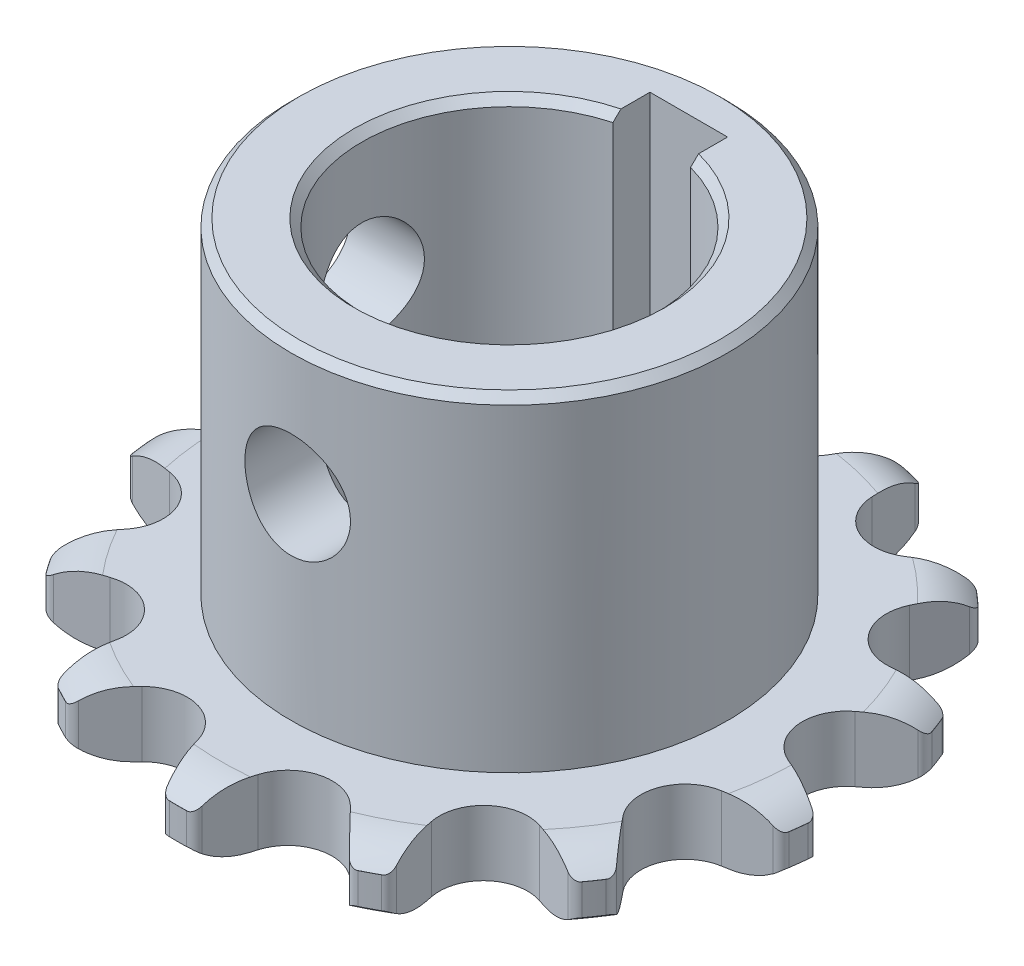
SolidWorks part; units mm, degrees
ref_plane "Alzado" through (0, 0, 0) normal (0, 0, 1) x (1, 0, 0)
ref_plane "Planta" through (0, 0, 0) normal (0, 1, 0) x (1, 0, 0)
ref_plane "Vista lateral" through (0, 0, 0) normal (1, 0, 0) x (0, 0, -1)
sketch "Croquis1" plane through (0, 0, 0) normal (0, 1, 0) x (1, 0, 0)
  circle A0 centre (0, 0) radius 14.05
  circle A1 centre (0, 0) radius 9.5
  dimension "D1" = 19
  dimension "D2" = 28.1
extrude "Saliente-Extruir1" add sketch "Croquis1" along normal blind 25.2
sketch "Croquis2" plane through (0, 25.2, 0) normal (0, 1, 0) x (1, 0, 0)
  line L0 (0, 11.55) -> (0, 14.05) construction
  line L1 (-2.5, 11.55) -> (2.5, 11.55)
  line L2 (-2.5, 11.55) -> (-2.5, 7.7298)
  line L3 (-2.5, 7.7298) -> (2.5, 7.7298)
  line L4 (2.5, 11.55) -> (2.5, 7.7298)
  circle A0 centre (0, 0) radius 14.05 construction
  point P4 (0, 11.55)
  dimension "D1" = 2.5
  dimension "D2" = 5
extrude "Cortar-Extruir1" cut sketch "Croquis2" against normal through all
sketch "Croquis4" plane through (0, 0, 0) normal (0, 0, 1) x (1, 0, 0)
  line L0 (0, 16.8) -> (0, 20.2) construction
  line L1 (9.5, 25.2) -> (-9.5, 25.2) construction
  circle A0 centre (0, 16.8) radius 3.4
  dimension "D2" = 6.8
  dimension "D1" = 5
extrude "Cortar-Extruir2" cut sketch "Croquis4" along normal through all
sketch "Croquis5" plane through (0, 0, 0) normal (1, 0, 0) x (0, 0, -1)
  line L0 (0, 16.8) -> (0, 20.2) construction
  line L1 (14.05, 25.2) -> (-14.05, 25.2) construction
  circle A0 centre (0, 16.8) radius 3.4
  dimension "D2" = 6.8
  dimension "D1" = 5
extrude "Cortar-Extruir3" cut sketch "Croquis5" against normal through all
sketch "Croquis6" plane through (0, 0, 0) normal (0, -1, 0) x (1, 0, 0)
  circle A0 centre (0, 0) radius 21.35
  circle A3 centre (0, 0) radius 12.05
  circle A4 centre (0, 0) radius 12.05
  dimension "D1" = 42.7
  dimension "D2" = 2
extrude "Saliente-Extruir2" add sketch "Croquis6" against normal blind 4.2
chamfer "Chaflán1" distance 0.5 angle 45 3 edges at (0, 25.2, 14.05) (0, 25.2, 9.5) (0, 0, 9.5)
sketch "Croquis8" plane through (0, 4.2, 0) normal (0, 1, 0) x (1, 0, 0)
  line L0 (0, 19.5) -> (0, 16.65) construction
  line L1 (2.5, 11.55) -> (-2.5, 11.55) construction
  circle A0 centre (0, 19.5) radius 2.85
  circle A1 centre (9.0621, 17.2664) radius 2.85
  circle A2 centre (16.0482, 11.0773) radius 2.85
  circle A3 centre (19.3578, 2.3505) radius 2.85
  circle A4 centre (18.2328, -6.9148) radius 2.85
  circle A5 centre (12.9309, -14.596) radius 2.85
  circle A6 centre (4.6667, -18.9334) radius 2.85
  circle A7 centre (-4.6667, -18.9334) radius 2.85
  circle A8 centre (-12.9309, -14.596) radius 2.85
  circle A9 centre (-18.2328, -6.9148) radius 2.85
  circle A10 centre (-19.3578, 2.3505) radius 2.85
  circle A11 centre (-16.0482, 11.0773) radius 2.85
  circle A12 centre (-9.0621, 17.2664) radius 2.85
  circle A13 centre (0, 0) radius 14.05 construction
  dimension "D2" = 5.7
  dimension "D4" = 4.6667
  dimension "D1" = 5.1
  dimension "D5" = 12.9309
  dimension "D6" = 16.0482
  dimension "D7" = 18.2328
  dimension "D8" = 19.3578
  dimension "D9" = 4.6667
  dimension "D10" = 9.0621
  dimension "D11" = 12.9309
  dimension "D12" = 16.0482
  dimension "D13" = 18.2328
  dimension "D14" = 19.3578
  dimension "D15" = 2.3505
  dimension "D3" = 9.0621
  dimension "D16" = 11.0773
  dimension "D17" = 17.2664
  dimension "D18" = 6.9148
  dimension "D19" = 14.596
  dimension "D20" = 18.9334
extrude "Cortar-Extruir4" cut sketch "Croquis8" against normal through all
sketch "Croquis9" plane through (0, 4.2, 0) normal (0, 1, 0) x (1, 0, 0)
  line L0 (2.4655, 18.0703) -> (4.1331, 20.9461)
  line L1 (6.0745, 20.4676) -> (6.2146, 17.1462)
  line L4 (2.2653, 21.2295) -> (3.6331, 21.8461)
  line L5 (3.6331, 21.8461) -> (4.1331, 20.9461)
  line L6 (6.0745, 20.4676) -> (6.5745, 21.216)
  line L7 (6.5745, 21.216) -> (7.8601, 19.8505)
  line L8 (13.3694, 17.6554) -> (13.3938, 16.6261)
  line L9 (10.5807, 14.8547) -> (13.3938, 16.6261)
  line L10 (11.8716, 17.7451) -> (13.3694, 17.6554)
  line L11 (15.6809, 15.7305) -> (16.1847, 13.924)
  line L12 (14.8904, 15.3002) -> (13.471, 12.2941)
  line L13 (14.8904, 15.3002) -> (15.6809, 15.7305)
  line L14 (20.0428, 9.42) -> (19.5862, 8.4973)
  line L15 (16.2721, 8.2361) -> (19.5862, 8.4973)
  line L16 (18.7583, 10.1955) -> (20.0428, 9.42)
  line L17 (21.1951, 6.6414) -> (20.8017, 4.8077)
  line L18 (20.2952, 6.6277) -> (17.6414, 4.6256)
  line L19 (20.2952, 6.6277) -> (21.1951, 6.6414)
  line L20 (22.1248, -0.9734) -> (21.2916, -1.5782)
  line L21 (18.2357, -0.2693) -> (21.2916, -1.5782)
  line L22 (21.3477, 0.3102) -> (22.1248, -0.9734)
  line L23 (21.8537, -3.9692) -> (20.6532, -5.41)
  line L24 (21.0506, -3.5631) -> (17.7703, -4.1026)
  line L25 (21.0506, -3.5631) -> (21.8537, -3.9692)
  line L26 (19.1382, -11.1438) -> (18.1193, -11.2921)
  line L27 (16.0218, -8.7131) -> (18.1193, -11.2921)
  line L28 (19.0466, -9.6461) -> (19.1382, -11.1438)
  line L29 (17.5059, -13.6705) -> (15.7733, -14.3884)
  line L30 (16.9835, -12.9376) -> (13.8283, -11.8909)
  line L31 (16.9835, -12.9376) -> (17.5059, -13.6705)
  line L32 (11.7672, -18.7613) -> (10.7962, -18.4192)
  line L33 (10.1374, -15.1607) -> (10.7962, -18.4192)
  line L34 (12.3822, -17.3926) -> (11.7672, -18.7613)
  line L35 (9.1477, -20.24) -> (7.28, -20.0705)
  line L36 (9.0257, -19.3483) -> (6.7183, -16.9552)
  line L37 (9.0257, -19.3483) -> (9.1477, -20.24)
  line L38 (1.7006, -22.0808) -> (0.9997, -21.3266)
  line L39 (1.9307, -18.1352) -> (0.9997, -21.3266)
  line L40 (2.8811, -21.1547) -> (1.7006, -22.0808)
  line L41 (-1.3061, -22.1728) -> (-2.8811, -21.1547)
  line L42 (-0.9997, -21.3266) -> (-1.9307, -18.1352)
  line L43 (-0.9997, -21.3266) -> (-1.3061, -22.1728)
  line L44 (-8.7557, -20.3419) -> (-9.0257, -19.3483)
  line L45 (-6.7183, -16.9552) -> (-9.0257, -19.3483)
  line L46 (-7.28, -20.0705) -> (-8.7557, -20.3419)
  line L47 (-11.4607, -19.0261) -> (-12.3822, -17.3926)
  line L48 (-10.7962, -18.4192) -> (-10.1374, -15.1607)
  line L49 (-10.7962, -18.4192) -> (-11.4607, -19.0261)
  line L50 (-17.2061, -13.9429) -> (-16.9835, -12.9376)
  line L51 (-13.8283, -11.8909) -> (-16.9835, -12.9376)
  line L52 (-15.7733, -14.3884) -> (-17.2061, -13.9429)
  line L53 (-18.9898, -11.5207) -> (-19.0466, -9.6461)
  line L54 (-18.1193, -11.2921) -> (-16.0218, -8.7131)
  line L55 (-18.1193, -11.2921) -> (-18.9898, -11.5207)
  line L56 (-21.7148, -4.3497) -> (-21.0506, -3.5631)
  line L57 (-17.7703, -4.1026) -> (-21.0506, -3.5631)
  line L58 (-20.6532, -5.41) -> (-21.7148, -4.3497)
  line L59 (-22.1686, -1.3761) -> (-21.3477, 0.3102)
  line L60 (-21.2916, -1.5782) -> (-18.2357, -0.2693)
  line L61 (-21.2916, -1.5782) -> (-22.1686, -1.3761)
  line L62 (-21.2489, 6.2399) -> (-20.2952, 6.6277)
  line L63 (-17.6414, 4.6256) -> (-20.2952, 6.6277)
  line L64 (-20.8017, 4.8077) -> (-21.2489, 6.2399)
  line L65 (-20.2688, 9.0838) -> (-18.7583, 10.1955)
  line L66 (-19.5862, 8.4973) -> (-16.2721, 8.2361)
  line L67 (-19.5862, 8.4973) -> (-20.2688, 9.0838)
  line L68 (-15.9152, 15.4) -> (-14.8904, 15.3002)
  line L69 (-13.471, 12.2941) -> (-14.8904, 15.3002)
  line L70 (-16.1847, 13.924) -> (-15.9152, 15.4)
  line L71 (-13.7257, 17.4627) -> (-11.8716, 17.7451)
  line L72 (-13.3938, 16.6261) -> (-10.5807, 14.8547)
  line L73 (-13.3938, 16.6261) -> (-13.7257, 17.4627)
  line L74 (-6.9354, 21.0322) -> (-6.0745, 20.4676)
  line L75 (-6.2146, 17.1462) -> (-6.0745, 20.4676)
  line L76 (-7.8601, 19.8505) -> (-6.9354, 21.0322)
  line L77 (-4.0381, 21.8411) -> (-2.2653, 21.2295)
  line L78 (-4.1331, 20.9461) -> (-2.4655, 18.0703)
  line L79 (-4.1331, 20.9461) -> (-4.0381, 21.8411)
  arc A0 (-2.2653, 21.2295) -> (2.2653, 21.2295) centre (0, 19.5) ccw construction
  arc A1 (7.8601, 19.8505) -> (2.2653, 21.2295) centre (0, 0) ccw construction
  arc A2 (10.5807, 14.8547) -> (11.8716, 17.7451) centre (9.0621, 17.2664) ccw
  arc A3 (7.8601, 19.8505) -> (11.8716, 17.7451) centre (9.0621, 17.2664) ccw construction
  arc A4 (7.8601, 19.8505) -> (6.2146, 17.1462) centre (9.0621, 17.2664) ccw
  arc A5 (2.4655, 18.0703) -> (2.2653, 21.2295) centre (0, 19.5) ccw
  arc A6 (16.1847, 13.924) -> (13.471, 12.2941) centre (16.0482, 11.0773) ccw
  arc A7 (16.2721, 8.2361) -> (18.7583, 10.1955) centre (16.0482, 11.0773) ccw
  arc A8 (20.8017, 4.8077) -> (17.6414, 4.6256) centre (19.3578, 2.3505) ccw
  arc A9 (18.2357, -0.2693) -> (21.3477, 0.3102) centre (19.3578, 2.3505) ccw
  arc A10 (20.6532, -5.41) -> (17.7703, -4.1026) centre (18.2328, -6.9148) ccw
  arc A11 (16.0218, -8.7131) -> (19.0466, -9.6461) centre (18.2328, -6.9148) ccw
  arc A12 (15.7733, -14.3884) -> (13.8283, -11.8909) centre (12.9309, -14.596) ccw
  arc A13 (10.1374, -15.1607) -> (12.3822, -17.3926) centre (12.9309, -14.596) ccw
  arc A14 (7.28, -20.0705) -> (6.7183, -16.9552) centre (4.6667, -18.9334) ccw
  arc A15 (1.9307, -18.1352) -> (2.8811, -21.1547) centre (4.6667, -18.9334) ccw
  arc A16 (-2.8811, -21.1547) -> (-1.9307, -18.1352) centre (-4.6667, -18.9334) ccw
  arc A17 (-6.7183, -16.9552) -> (-7.28, -20.0705) centre (-4.6667, -18.9334) ccw
  arc A18 (-12.3822, -17.3926) -> (-10.1374, -15.1607) centre (-12.9309, -14.596) ccw
  arc A19 (-13.8283, -11.8909) -> (-15.7733, -14.3884) centre (-12.9309, -14.596) ccw
  arc A20 (-19.0466, -9.6461) -> (-16.0218, -8.7131) centre (-18.2328, -6.9148) ccw
  arc A21 (-17.7703, -4.1026) -> (-20.6532, -5.41) centre (-18.2328, -6.9148) ccw
  arc A22 (-21.3477, 0.3102) -> (-18.2357, -0.2693) centre (-19.3578, 2.3505) ccw
  arc A23 (-17.6414, 4.6256) -> (-20.8017, 4.8077) centre (-19.3578, 2.3505) ccw
  arc A24 (-18.7583, 10.1955) -> (-16.2721, 8.2361) centre (-16.0482, 11.0773) ccw
  arc A25 (-13.471, 12.2941) -> (-16.1847, 13.924) centre (-16.0482, 11.0773) ccw
  arc A26 (-11.8716, 17.7451) -> (-10.5807, 14.8547) centre (-9.0621, 17.2664) ccw
  arc A27 (-6.2146, 17.1462) -> (-7.8601, 19.8505) centre (-9.0621, 17.2664) ccw
  arc A28 (-2.2653, 21.2295) -> (-2.4655, 18.0703) centre (0, 19.5) ccw
  point P10 (5.1094, 20.7296)
  dimension "D1" = 1
  dimension "D2" = 1
  dimension "D3" = 0.5
  dimension "D4" = 0.9
  dimension "D5" = 0.9
  dimension "D6" = 0.5
extrude "Cortar-Extruir8" cut sketch "Croquis9" against normal blind 4.2
fillet "Redondeo3" radius 0.6 26 edges at (4.1331, 2.1, -20.9461) (-4.1331, 2.1, -20.9461) (-6.0745, 2.1, -20.4676) (-13.3938, 2.1, -16.6261) (-14.8904, 2.1, -15.3002) (-19.5862, 2.1, -8.4973) (-20.2952, 2.1, -6.6277) (-21.2916, 2.1, 1.5782) (-21.0506, 2.1, 3.5631) (-18.1193, 2.1, 11.2921) (-16.9835, 2.1, 12.9376) (-10.7962, 2.1, 18.4192) (-9.0257, 2.1, 19.3483) (-0.9997, 2.1, 21.3266) (0.9997, 2.1, 21.3266) (9.0257, 2.1, 19.3483) (10.7962, 2.1, 18.4192) (16.9835, 2.1, 12.9376) (18.1193, 2.1, 11.2921) (21.0506, 2.1, 3.5631) (21.2916, 2.1, 1.5782) (20.2952, 2.1, -6.6277) (19.5862, 2.1, -8.4973) (13.3938, 2.1, -16.6261) (6.0745, 2.1, -20.4676) (14.8904, 2.1, -15.3002)
sketch "Croquis10" plane through (0, 0, 0) normal (1, 0, 0) x (0, 0, -1)
  line L1 (-21.3426, 0) -> (-21.3426, 4.2) construction
  line L2 (-18.1352, 4.2) -> (-20.9109, 4.2) construction
  line L3 (-15.1607, 4.2) -> (-17.9947, 4.2) construction
  line L4 (-15.1607, 0) -> (-17.9947, 0) construction
  line L6 (-18.6374, 0) -> (-17.9947, 0) construction
  line L8 (-21.4426, 0) -> (-18.5876, 0)
  line L10 (-21.4426, 4.2) -> (-18.5876, 4.2)
  line L11 (0, 0) -> (0, 24.7) construction
  line L12 (-14.05, 24.7) -> (14.05, 24.7) construction
  line L13 (-21.3426, 3.1) -> (-21.4426, 3.1)
  line L14 (-21.4426, 3.1) -> (-21.4426, 4.2)
  line L15 (-21.3426, 1.1) -> (-21.4426, 1.1)
  line L16 (-21.4426, 1.1) -> (-21.4426, 0)
  arc A0 (-18.5876, 0) -> (-21.3426, 1.1) centre (-18.5876, 4) cw
  arc A1 (-21.3426, 3.1) -> (-18.5876, 4.2) centre (-18.5876, 0.2) cw
  point P18 (-21.3426, 2.1)
  dimension "D3" = 4
  dimension "D4" = 4
  dimension "D1" = 2
  dimension "D2" = 1
  dimension "D5" = 0.1
  dimension "D6" = 0.1
revolve "Cortar-Revolución1" cut sketch "Croquis10" angle 360 about L11
